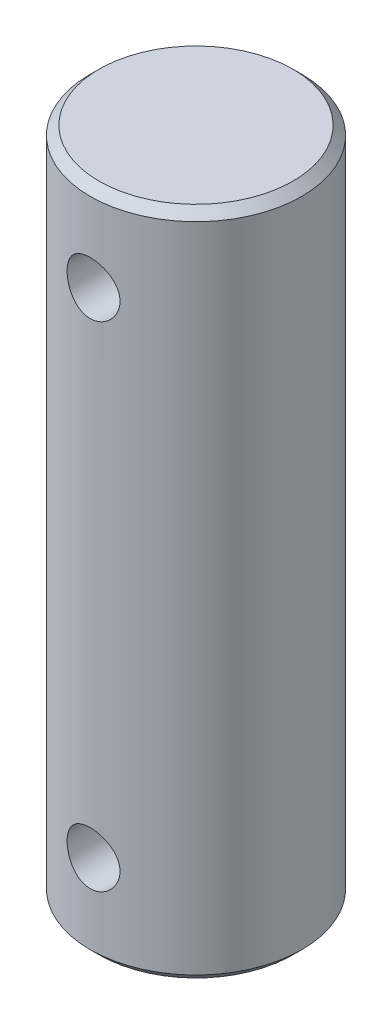
SolidWorks part; units mm, degrees
ref_plane "Front Plane" through (0, 0, 0) normal (0, 0, 1) x (1, 0, 0)
ref_plane "Top Plane" through (0, 0, 0) normal (0, 1, 0) x (1, 0, 0)
ref_plane "Right Plane" through (0, 0, 0) normal (1, 0, 0) x (0, 0, -1)
sketch "Sketch1" plane through (0, 0, 0) normal (0, 1, 0) x (1, 0, 0)
  circle A0 centre (0, 0) radius 6
extrude "Boss-Extrude1" add sketch "Sketch1" along normal blind 38
sketch "Sketch2" plane through (0, 0, 0) normal (0, 0, 1) x (1, 0, 0)
  circle A0 centre (0, 5) radius 1.5
  circle A1 centre (0, 33) radius 1.5
  dimension "D1" = 3
  dimension "D2" = 3
  dimension "D3" = 33
  dimension "D4" = 5
extrude "Cut-Extrude1" cut sketch "Sketch2" against normal through all both and the other way through all
chamfer "Chamfer1" distance 0.5 angle 45 2 edges at (0, 38, 6) (0, 0, 6)
